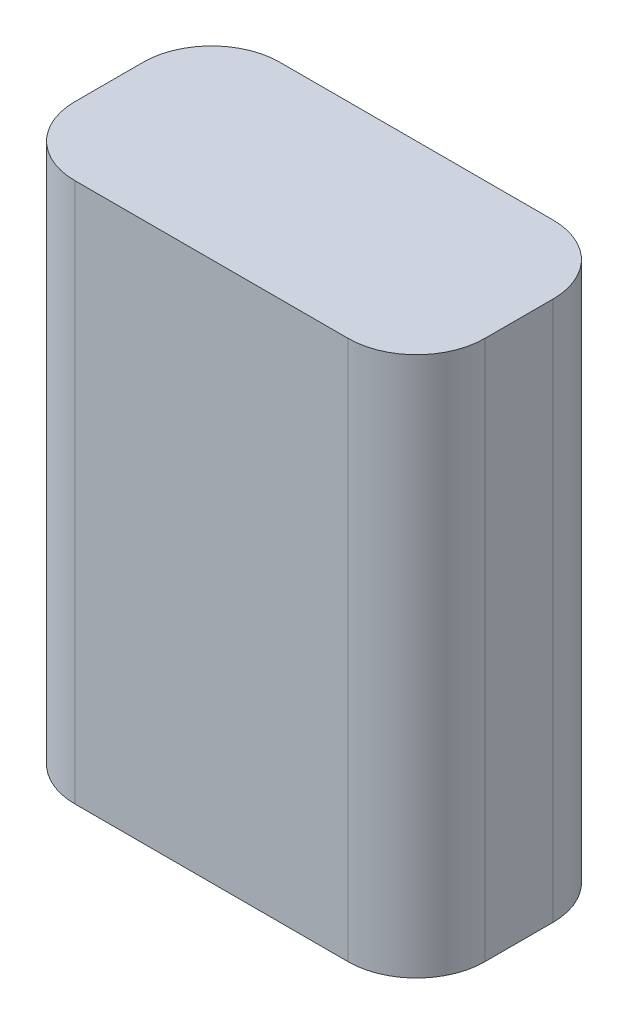
SolidWorks part; units mm, degrees
material "PET"
ref_plane "Front" through (0, 0, 0) normal (0, 0, 1) x (1, 0, 0)
ref_plane "Top" through (0, 0, 0) normal (0, 1, 0) x (1, 0, 0)
ref_plane "Right" through (0, 0, 0) normal (1, 0, 0) x (0, 0, -1)
sketch "Sketch1" plane through (0, 0, 0) normal (0, 1, 0) x (1, 0, 0)
  line L1 (-5, 3.75) -> (5, 3.75)
  line L2 (-7.5, 1.25) -> (-7.5, -1.25)
  line L3 (-5, -3.75) -> (5, -3.75)
  line L4 (7.5, 1.25) -> (7.5, -1.25)
  line L5 (-7.5, 3.75) -> (7.5, -3.75) construction
  line L6 (-7.5, -3.75) -> (7.5, 3.75) construction
  arc A0 (-5, 3.75) -> (-7.5, 1.25) centre (-5, 1.25) ccw
  arc A1 (-7.5, -1.25) -> (-5, -3.75) centre (-5, -1.25) ccw
  arc A2 (5, -3.75) -> (7.5, -1.25) centre (5, -1.25) ccw
  arc A3 (5, 3.75) -> (7.5, 1.25) centre (5, 1.25) cw
  point P0 (0, 0)
  dimension "D3" = 2.5
  dimension "D1" = 15
  dimension "D2" = 7.5
extrude "Boss-Extrude1" add sketch "Sketch1" along normal blind 19.75
